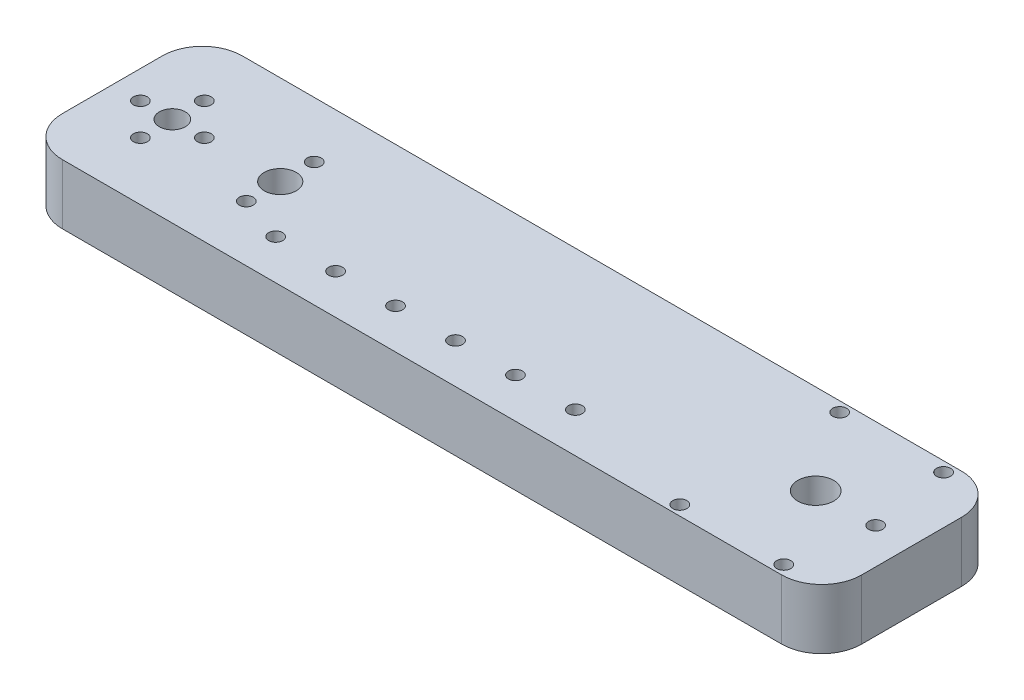
SolidWorks part; units mm, degrees
material "ABS"
ref_plane "Alzado" through (0, 0, 0) normal (0, 0, 1) x (1, 0, 0)
ref_plane "Planta" through (0, 0, 0) normal (0, 1, 0) x (1, 0, 0)
ref_plane "Vista lateral" through (0, 0, 0) normal (1, 0, 0) x (0, 0, -1)
sketch "Croquis1" plane through (0, 0, 0) normal (0, 1, 0) x (1, 0, 0)
  line L1 (-100, -22.5) -> (100, -22.5)
  line L2 (-100, -22.5) -> (-100, 22.5)
  line L3 (-100, 22.5) -> (100, 22.5)
  line L4 (100, -22.5) -> (100, 22.5)
  line L5 (-100, -22.5) -> (100, 22.5) construction
  line L6 (-100, 22.5) -> (100, -22.5) construction
  point P0 (0, 0)
  dimension "D1" = 200
  dimension "D2" = 45
extrude "Saliente-Extruir1" add sketch "Croquis1" along normal blind 10
sketch "Croquis2" plane through (0, 0, 0) normal (0, -1, 0) x (1, 0, 0)
  line L0 (-88.25, 0) -> (-81.75, 0)
  line L1 (-100, -22.5) -> (-100, 22.5) construction
  line L2 (-85, -8) -> (-85, 8)
  circle A0 centre (-85, 0) radius 3.25
  point P6 (-85, 0)
  point P11 (-85, 0)
  dimension "D1" = 6.5
  dimension "D3" = 15
  dimension "D4" = 16
extrude "Cortar-Extruir1" cut sketch "Croquis2" against normal up to next
sketch "Croquis4" plane through (0, 10, 0) normal (0, 1, 0) x (1, 0, 0)
  line L0 (100, -22.5) -> (100, 22.5) construction
  circle A0 centre (76, 0) radius 4.5
  dimension "D1" = 9
  dimension "D2" = 24
extrude "Cortar-Extruir2" cut sketch "Croquis4" against normal up to next contours A0
sketch "Croquis6" plane through (0, 0, 0) normal (0, -1, 0) x (1, 0, 0)
  line L0 (-93, 0) -> (-77, 0)
  line L1 (-85, -8) -> (-85, 8)
  circle A0 centre (-85, 0) radius 11
  circle A1 centre (-77, 0) radius 1.75
  circle A2 centre (-93, 0) radius 1.75
  circle A3 centre (-85, 8) radius 1.75
  circle A4 centre (-85, -8) radius 1.75
  point P7 (-85, 0)
  point P12 (-85, 0)
  dimension "D1" = 22
  dimension "D3" = 3.5
  dimension "D4" = 3.5
  dimension "D6" = 3.5
  dimension "D7" = 3.5
  dimension "D2" = 16
  dimension "D5" = 16
extrude "Cortar-Extruir3" cut sketch "Croquis6" against normal up to next
sketch "Croquis7" plane through (0, 0, 0) normal (0, -1, 0) x (1, 0, 0)
  line L0 (-100, -22.5) -> (-100, 22.5) construction
  line L1 (-58, -8.5) -> (-58, 8.5)
  circle A0 centre (-58, 0) radius 12.5
  circle A1 centre (-85, 0) radius 11
  circle A2 centre (-58, 0) radius 4
  circle A3 centre (-58, 8.5) radius 1.75
  circle A4 centre (-58, -8.5) radius 1.75
  point P11 (-58, 0)
  dimension "D1" = 25
  dimension "D2" = 42
  dimension "D3" = 22
  dimension "D4" = 8
  dimension "D6" = 3.5
  dimension "D7" = 3.5
  dimension "D5" = 17
extrude "Cortar-Extruir4" cut sketch "Croquis7" against normal up to next
sketch "Croquis9" plane through (0, 0, 0) normal (0, -1, 0) x (1, 0, 0)
  line L1 (-100, -22.5) -> (100, -22.5)
  line L2 (-100, -22.5) -> (-100, 22.5)
  line L3 (-100, 22.5) -> (100, 22.5)
  line L4 (100, -22.5) -> (100, 22.5)
  line L5 (-100, -22.5) -> (100, 22.5) construction
  line L6 (-100, 22.5) -> (100, -22.5) construction
  line L7 (-97, -17.5) -> (97, -17.5)
  line L8 (-97, -17.5) -> (-97, 17.5)
  line L9 (-97, 17.5) -> (97, 17.5)
  line L10 (97, -17.5) -> (97, 17.5)
  line L11 (-97, -17.5) -> (97, 17.5) construction
  line L12 (-97, 17.5) -> (97, -17.5) construction
  point P0 (0, 0)
  point P6 (0, 0)
  dimension "D1" = 45
  dimension "D2" = 200
  dimension "D3" = 3
  dimension "D4" = 5
extrude "Saliente-Extruir2" add sketch "Croquis9" along normal blind 5
fillet "Redondeo1" radius 10 4 edges at (-100, 2.5, 22.5) (-100, 2.5, -22.5) (100, 2.5, -22.5) (100, 2.5, 22.5)
fillet "Redondeo2" radius 10 4 edges at (97, -2.5, -17.5) (-97, -2.5, -17.5) (-97, -2.5, 17.5) (97, -2.5, 17.5)
sketch "Croquis10" plane through (0, -5, 0) normal (0, -1, 0) x (1, 0, 0)
  line L0 (100, 0) -> (50, 0)
  line L1 (100, -12.5) -> (100, 12.5) construction
  circle A0 centre (62, 20) radius 1.75
  circle A1 centre (88, 20) radius 1.75
  circle A2 centre (62, -20) radius 1.75
  circle A3 centre (88, -20) radius 1.75
  dimension "D2" = 12
  dimension "D3" = 12
  dimension "D4" = 12
  dimension "D5" = 12
  dimension "D6" = 3.5
  dimension "D8" = 20
  dimension "D10" = 20
  dimension "D11" = 3.5
  dimension "D12" = 3.5
  dimension "D13" = 3.5
  dimension "D1" = 50
  dimension "D7" = 20
  dimension "D9" = 20
extrude "Cortar-Extruir5" cut sketch "Croquis10" against normal blind 15 contours A1 | A0 | A2 | A3
sketch "Croquis11" plane through (0, 0, 0) normal (0, -1, 0) x (1, 0, 0)
  circle A0 centre (76, 0) radius 9.5
  circle A1 centre (76, 0) radius 8
  dimension "D1" = 19
  dimension "D2" = 16
extrude "Saliente-Extruir3" add sketch "Croquis11" along normal blind 4
fillet "Redondeo3" radius 3 1 edges at (76, 0, -9.5)
sketch "Croquis12" plane through (0, 10, 0) normal (0, 1, 0) x (1, 0, 0)
  circle A0 centre (91, 0) radius 1.75
  circle A1 centre (76, 0) radius 4.5 construction
  dimension "D1" = 3.5
  dimension "D2" = 15
extrude "Cortar-Extruir6" cut sketch "Croquis12" against normal up to next contours A0
sketch "Croquis13" plane through (0, 10, 0) normal (0, 1, 0) x (1, 0, 0)
  line L0 (-90, -22.5) -> (90, -22.5) construction
  line L1 (28.3534, -12.5) -> (13.3534, -12.5) construction
  circle A0 centre (28.3534, -12.5) radius 1.75
  circle A1 centre (13.3534, -12.5) radius 1.75
  circle A2 centre (-1.6466, -12.5) radius 1.75
  circle A3 centre (-16.6466, -12.5) radius 1.75
  circle A4 centre (-31.6466, -12.5) radius 1.75
  circle A5 centre (-46.6466, -12.5) radius 1.75
  dimension "D2" = 3.5
  dimension "D1" = 10
  dimension "D4" = 15
  dimension "D3" = 6
extrude "Cortar-Extruir7" cut sketch "Croquis13" against normal blind 10
